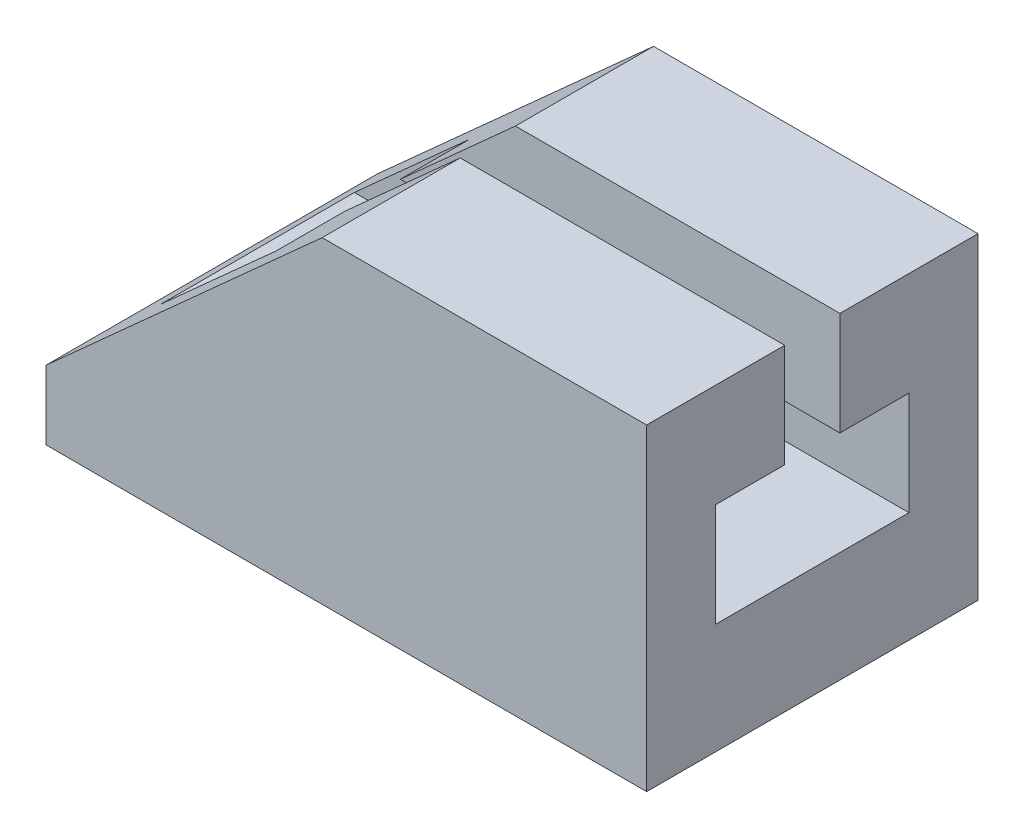
SolidWorks part; units mm, degrees
ref_plane "Front Plane" through (0, 0, 0) normal (0, 0, 1) x (1, 0, 0)
ref_plane "Top Plane" through (0, 0, 0) normal (0, 1, 0) x (1, 0, 0)
ref_plane "Right Plane" through (0, 0, 0) normal (1, 0, 0) x (0, 0, -1)
sketch "Sketch2" plane through (0, 0, 0) normal (0, 0, 1) x (1, 0, 0)
  line L0 (0, 0) -> (0, 46)
  line L1 (0, 46) -> (-47, 46)
  line L2 (-47, 46) -> (-87, 10)
  line L3 (-87, 10) -> (-87, 0)
  line L4 (-87, 0) -> (0, 0)
  dimension "D1" = 87
  dimension "D2" = 46
  dimension "D3" = 47
  dimension "D4" = 10
extrude "Boss-Extrude1" add sketch "Sketch2" along normal blind 48
sketch "Sketch3" plane through (0, 0, 0) normal (1, 0, 0) x (0, 0, -1)
  line L0 (-28, 46) -> (-20, 46)
  line L1 (-48, 46) -> (0, 46) construction
  line L2 (-24, 46) -> (-24, 0) construction
  line L3 (-48, 0) -> (0, 0) construction
  line L4 (-28, 46) -> (-28, 31)
  line L5 (-38, 31) -> (-28, 31)
  line L6 (-38, 31) -> (-38, 16)
  line L7 (-38, 16) -> (-10, 16)
  line L8 (-10, 31) -> (-10, 16)
  line L9 (-10, 31) -> (-20, 31)
  line L10 (-20, 46) -> (-20, 31)
  point P13 (-24, 16)
  dimension "D1" = 8
  dimension "D2" = 15
  dimension "D3" = 10
  dimension "D4" = 15
extrude "Cut-Extrude1" cut sketch "Sketch3" against normal through all
